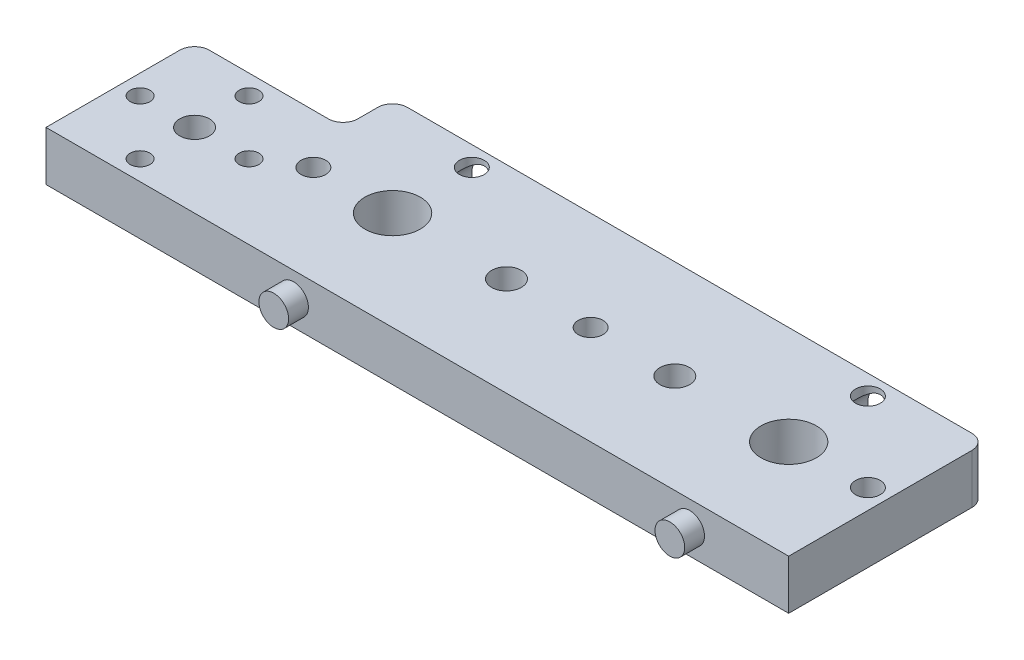
SolidWorks part; units mm, degrees
ref_plane "前视基准面" through (0, 0, 0) normal (0, 0, 1) x (1, 0, 0)
ref_plane "上视基准面" through (0, 0, 0) normal (0, 1, 0) x (1, 0, 0)
ref_plane "右视基准面" through (0, 0, 0) normal (1, 0, 0) x (0, 0, -1)
other "Configuration Table"
sketch "草图1" plane through (0, 0, 0) normal (0, 1, 0) x (1, 0, 0)
  line L0 (0, 10) -> (0, -10) construction
  line L1 (-30, 10) -> (30, 10)
  line L2 (-30, 10) -> (-30, -10)
  line L3 (-30, -10) -> (30, -10)
  line L4 (30, 10) -> (30, -10)
  line L5 (-30, 0) -> (30, 0) construction
  line L7 (-30, -10) -> (-45, -10)
  line L10 (-30, -10) -> (-30, 5)
  line L11 (-30, 5) -> (-45, 5)
  line L12 (-45, -10) -> (-45, 5)
  circle A1 centre (15.2, 0) radius 4.1
  circle A2 centre (-15.2, 0) radius 4.1
  circle A3 centre (15.2, 0) radius 2.9
  circle A4 centre (-15.2, 0) radius 2.9
  dimension "D3" = 15.2
  dimension "D4" = 8.2
  dimension "D5" = 5.8
  dimension "D1" = 60
  dimension "D2" = 20
  dimension "D6" = 15
  dimension "D7" = 15
extrude "凸台-拉伸1" add sketch "草图1" along normal blind 5 contours L2 L1 L4 L3 | L10 L7 L12 L11
sketch "草图2" plane through (0, 5, 0) normal (0, 1, 0) x (1, 0, 0)
  line L0 (0, 10) -> (0, -10) construction
  line L1 (-30, 10) -> (30, 10) construction
  line L2 (-37.5, 5) -> (-37.5, -10) construction
  line L3 (30, 10) -> (30, -10) construction
  line L4 (-30, 10) -> (-30, -10) construction
  line L5 (-45, -10) -> (30, -10) construction
  line L6 (-30, -10) -> (30, -10) construction
  line L7 (-30, 5) -> (-45, 5) construction
  line L9 (-45, -10) -> (-45, 5) construction
  line L10 (-45, -2.5) -> (-30, -2.5) construction
  circle A0 centre (8.5, 0) radius 1.5
  circle A1 centre (-8.5, 0) radius 1.5
  circle A2 centre (0, 0) radius 1.25
  circle A3 centre (20, 0) radius 4.1
  circle A4 centre (20, 0) radius 2.8
  circle A5 centre (-20, 0) radius 4.1
  circle A6 centre (-20, 0) radius 2.8
  circle A7 centre (20, 8) radius 1.25
  circle A8 centre (28, 0) radius 1.25
  circle A9 centre (-28, 0) radius 1.25
  circle A10 centre (-20, 8) radius 1.25
  circle A11 centre (-37.5, -2.5) radius 1.5
  circle A12 centre (-32, -2.5) radius 1
  circle A13 centre (-37.5, -8) radius 1
  circle A14 centre (-43, -2.5) radius 1
  circle A15 centre (-37.5, 3) radius 1
  point P12 (30, 0)
  point P36 (0, -10)
  dimension "D1" = 3
  dimension "D3" = 2.5
  dimension "D4" = 5.6
  dimension "D5" = 8.2
  dimension "D7" = 2.5
  dimension "D8" = 2.5
  dimension "D11" = 3
  dimension "D12" = 2
  dimension "D2" = 17
  dimension "D6" = 20
  dimension "D9" = 8
  dimension "D10" = 8
  dimension "D13" = 5.5
  dimension "D14" = 4
extrude "切除-拉伸1" cut sketch "草图2" along direction (0, -1, 0) on the side against the normal up to surface (5 mm away) contours A1 | A0 | A2 | A10 | A9 | A7 | A8 | A6 | A4 | A14 | A11 | A13 | A12 | A15
fillet "圆角1" radius 1.5 4 edges at (-30, 2.5, -10) (30, 2.5, -10) (-30, 2.5, -5) (-45, 2.5, -5)
sketch "草图4" plane through (0, 0, 10) normal (0, 0, 1) x (1, 0, 0)
  line L0 (30, 2.5) -> (-45, 2.5) construction
  line L1 (30, 5) -> (30, 0) construction
  line L2 (-45, 5) -> (-45, 0) construction
  line L3 (0, 0) -> (0, 5) construction
  line L4 (-45, 5) -> (30, 5) construction
  circle A0 centre (20, 2.5) radius 1.5
  circle A1 centre (-20, 2.5) radius 1.5
  dimension "D1" = 3
  dimension "D2" = 3
  dimension "D3" = 20
  dimension "D4" = 20
extrude "凸台-拉伸2" add sketch "草图4" along normal blind 2
sketch "草图5" plane through (0, 0, -10) normal (0, 0, -1) x (-1, 0, 0)
  line L0 (-28.5, 2.5) -> (28.5, 2.5) construction
  line L1 (-28.5, 5) -> (-28.5, 0) construction
  line L2 (28.5, 0) -> (28.5, 5) construction
  line L3 (0, 5) -> (0, 0) construction
  line L4 (28.5, 5) -> (-28.5, 5) construction
  line L5 (28.5, 0) -> (-28.5, 0) construction
  circle A0 centre (-20, 2.5) radius 2
  circle A2 centre (20, 2.5) radius 2
  dimension "D1" = 4
  dimension "D3" = 20
extrude "切除-拉伸2" cut sketch "草图5" against normal blind 5
